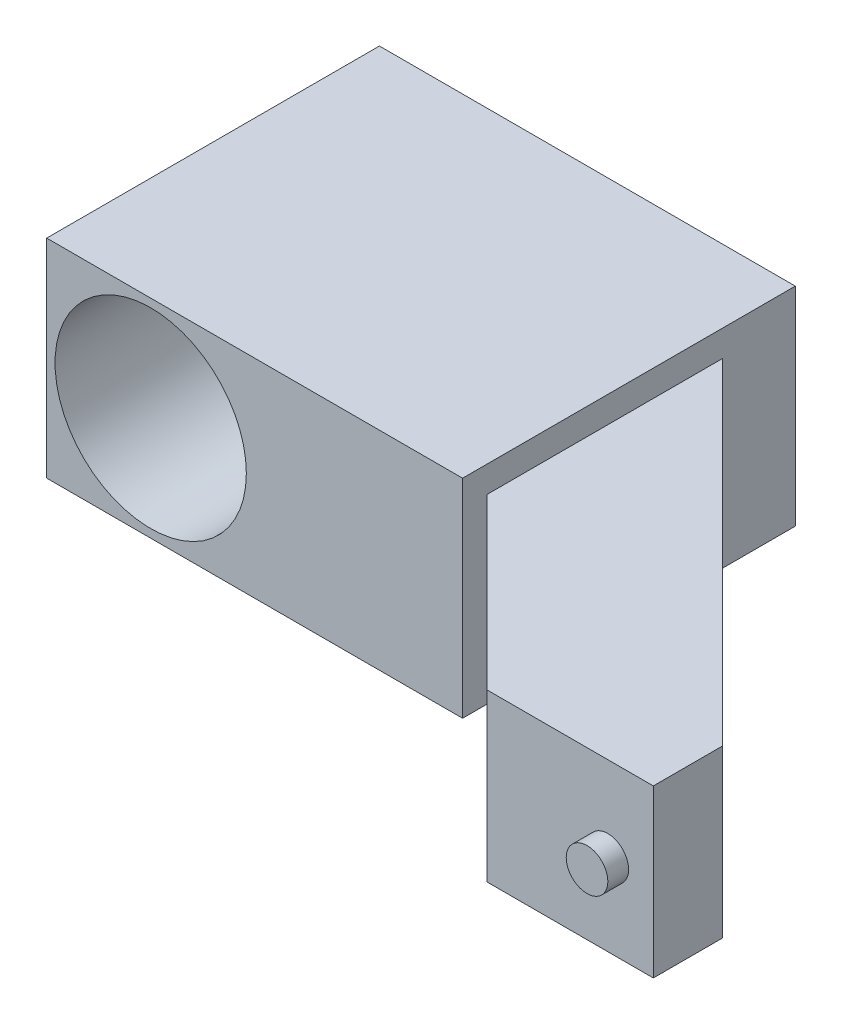
SolidWorks part; units mm, degrees
ref_plane "Ön Düzlem" through (0, 0, 0) normal (0, 0, 1) x (1, 0, 0)
ref_plane "Üst Düzlem" through (0, 0, 0) normal (0, 1, 0) x (1, 0, 0)
ref_plane "Sağ Düzlem" through (0, 0, 0) normal (1, 0, 0) x (0, 0, -1)
sketch "Çizim1" plane through (0, 0, 0) normal (0, 0, 1) x (1, 0, 0)
  line L1 (-100, 24.9863) -> (0, 24.9863)
  line L2 (-100, 24.9863) -> (-100, -25.0137)
  line L3 (-100, -25.0137) -> (0, -25.0137)
  line L4 (0, 24.9863) -> (0, -25.0137)
  dimension "D1" = 100
  dimension "D2" = 50
extrude "Yükseklik-Ekstrüzyon1" add sketch "Çizim1" along normal blind 80
ref_plane "Düzlem2" through (0, 0, 0) normal (0.7071, 0, 0.7071) x (0, 1, 0)
sketch "Çizim2" plane through (0, 0, 0) normal (0.7071, 0, 0.7071) x (0, 1, 0)
  line L1 (18.6574, 12.3854) -> (-21.3426, 12.3854)
  line L2 (18.6574, 12.3854) -> (18.6574, 52.3854)
  line L3 (18.6574, 52.3854) -> (-21.3426, 52.3854)
  line L4 (-21.3426, 12.3854) -> (-21.3426, 52.3854)
  dimension "D1" = 40
  dimension "D2" = 40
extrude "Yükseklik-Ekstrüzyon6" add sketch "Çizim2" along normal blind 150
ref_plane "Düzlem3" through (0, 0, 114.8238) normal (0, 0, 1) x (0, 1, 0)
sketch "Çizim11" plane through (0, 0, 114.8238) normal (0, 0, 1) x (0, 1, 0)
  line L0 (18.6574, -97.3082) -> (-21.3426, -97.3082)
  line L1 (-21.3426, -97.3082) -> (-41.21, -31.823)
  line L2 (-41.21, -31.823) -> (29.3627, -31.823)
  line L3 (29.3627, -31.823) -> (18.6574, -97.3082)
extrude "Kes-Ekstrüzyon4" cut sketch "Çizim11" along normal blind 50
sketch "Çizim12" plane through (0, 0, 114.8238) normal (0, 0, 1) x (1, 0, 0)
  circle A0 centre (69.7459, -1.723) radius 5
extrude "Yükseklik-Ekstrüzyon9" add sketch "Çizim12" along normal blind 5
sketch "Çizim13" plane through (0, 0, 80) normal (0, 0, 1) x (1, 0, 0)
  line L0 (-50, 24.9863) -> (-50, -25.0137)
  line L1 (0, 24.9863) -> (-100, 24.9863) construction
  line L2 (-100, -25.0137) -> (0, -25.0137) construction
  line L3 (-50, 24.9863) -> (-100, -25.0137) construction
  line L4 (-100, -25.0137) -> (-100, 24.9863) construction
  line L5 (-100, 24.9863) -> (-50, -25.0137) construction
  circle A0 centre (-75, -0.0137) radius 23
extrude "Kes-Ekstrüzyon9" cut sketch "Çizim13" against normal blind 78 contours A0
sketch "Çizim14" plane through (0, 0, 0) normal (0, 0, -1) x (-1, 0, 0)
  line L0 (50, -25.0137) -> (50, 24.9863)
  line L1 (100, -25.0137) -> (0, -25.0137) construction
  line L2 (0, 24.9863) -> (100, 24.9863) construction
  line L4 (100, 24.9863) -> (100, -25.0137) construction
  circle A0 centre (75, -0.0137) radius 2
extrude "Kes-Ekstrüzyon10" cut sketch "Çizim14" against normal blind 78 contours A0
sketch "Çizim15" plane through (0, 0, 114.8238) normal (0, 0, 1) x (1, 0, 0)
  line L0 (97.3082, 18.6574) -> (97.3082, -21.3426)
  line L1 (97.3082, -21.3426) -> (80.6865, -21.3426)
  line L2 (97.3082, -21.3426) -> (40.7397, -21.3426) construction
  line L3 (80.6865, -21.3426) -> (80.6865, 18.6574)
  line L4 (40.7397, 18.6574) -> (97.3082, 18.6574) construction
  line L5 (97.3082, 18.6574) -> (80.6865, 18.6574)
extrude "Kes-Ekstrüzyon15" cut sketch "Çizim15" against normal blind 20
